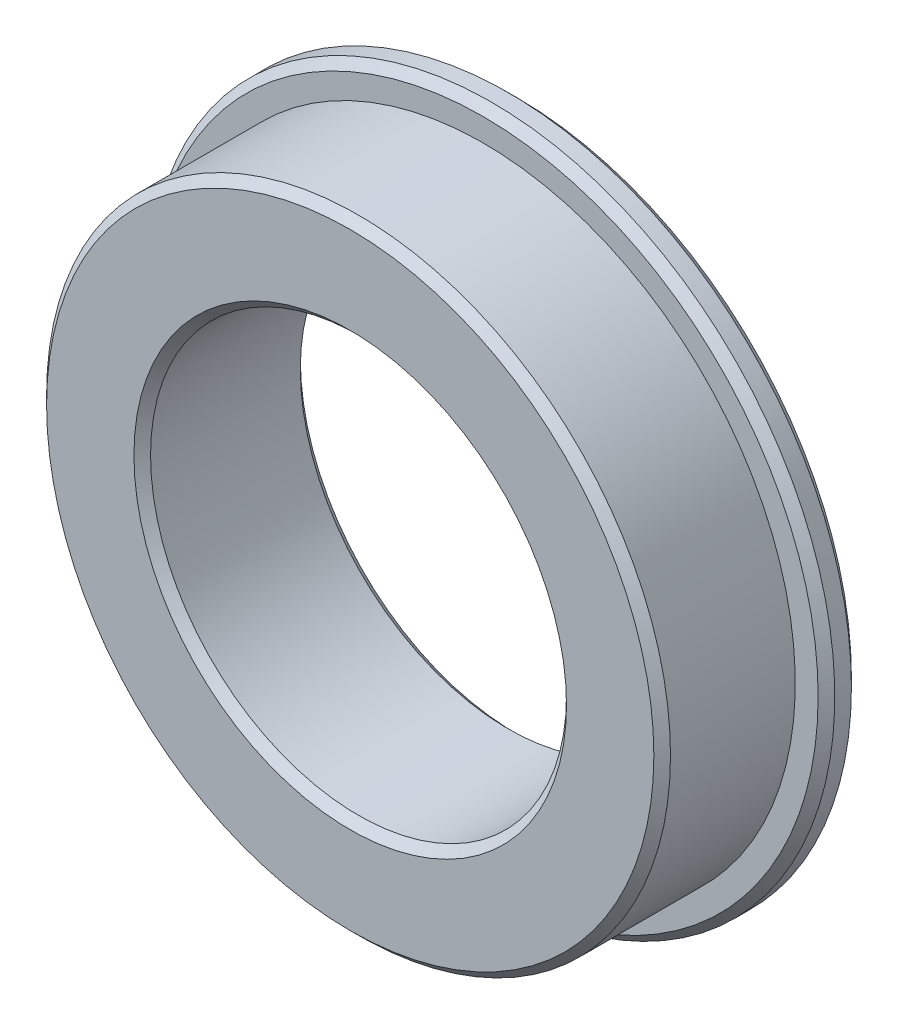
SolidWorks part; units mm, degrees
ref_plane "前视基准面" through (0, 0, 0) normal (0, 0, 1) x (1, 0, 0)
ref_plane "上视基准面" through (0, 0, 0) normal (0, 1, 0) x (1, 0, 0)
ref_plane "右视基准面" through (0, 0, 0) normal (1, 0, 0) x (0, 0, -1)
sketch "草图1" plane through (0, 0, 0) normal (0, 0, 1) x (1, 0, 0)
  circle A0 centre (0, 0) radius 5
  circle A1 centre (0, 0) radius 7.5
  dimension "D1" = 10
  dimension "D2" = 15
extrude "凸台-拉伸1" add sketch "草图1" along normal blind 4
sketch "草图2" plane through (0, 0, 0) normal (0, 0, -1) x (-1, 0, 0)
  circle A0 centre (0, 0) radius 8.25
  circle A1 centre (0, 0) radius 7.5 construction
  circle A2 centre (0, 0) radius 7.5
  dimension "D1" = 16.5
extrude "凸台-拉伸2" add sketch "草图2" against normal blind 0.8
chamfer "倒角1" distance 0.2 angle 45 5 edges at (5, 0, 4) (5, 0, 0) (-8.25, 0, 0.8) (-8.25, 0, 0) (7.5, 0, 4)
